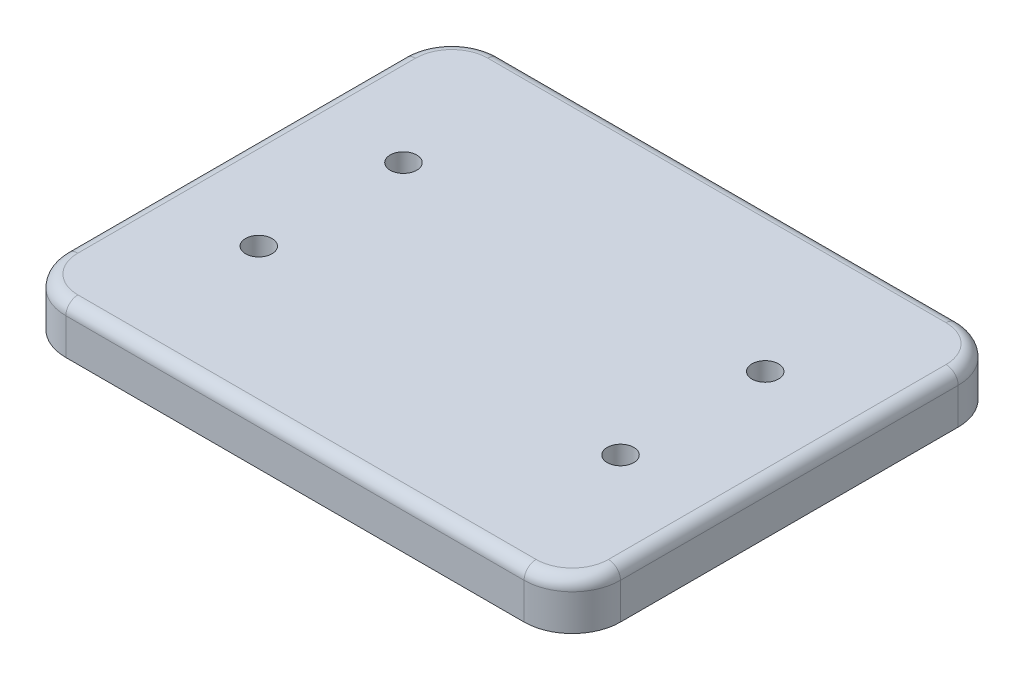
SolidWorks part; units mm, degrees
ref_plane "Front Plane" through (0, 0, 0) normal (0, 0, 1) x (1, 0, 0)
ref_plane "Top Plane" through (0, 0, 0) normal (0, 1, 0) x (1, 0, 0)
ref_plane "Right Plane" through (0, 0, 0) normal (1, 0, 0) x (0, 0, -1)
sketch "Sketch1" plane through (0, 0, 0) normal (0, 1, 0) x (1, 0, 0)
  line L0 (-115, 0) -> (115, 0) construction
  line L1 (-95, 90) -> (95, 90)
  line L2 (-115, 70) -> (-115, -70)
  line L3 (-95, -90) -> (95, -90)
  line L4 (115, 70) -> (115, -70)
  line L5 (-115, 90) -> (115, -90) construction
  line L6 (-115, -90) -> (115, 90) construction
  line L7 (0, 90) -> (0, -90) construction
  arc A0 (-95, -90) -> (-115, -70) centre (-95, -70) cw
  arc A1 (95, -90) -> (115, -70) centre (95, -70) ccw
  arc A2 (95, 90) -> (115, 70) centre (95, 70) cw
  arc A3 (-95, 90) -> (-115, 70) centre (-95, 70) ccw
  point P0 (0, 0)
  dimension "D3" = 20
  dimension "D1" = 230
  dimension "D2" = 180
extrude "Boss-Extrude1" add sketch "Sketch1" along normal blind 20
fillet "Fillet1" radius 5 8 edges at (-115, 20, 0) (-109.1421, 20, -84.1421) (0, 20, -90) (109.1421, 20, -84.1421) (115, 20, 0) (109.1421, 20, 84.1421) (0, 20, 90) (-109.1421, 20, 84.1421)
sketch "Sketch4" plane through (0, 0, 0) normal (0, 1, 0) x (1, 0, 0)
  line L0 (-115, 0) -> (115, 0) construction
  line L1 (0, 90) -> (0, -90) construction
  circle A0 centre (-75, 30) radius 5.5
  circle A1 centre (75, 30) radius 5.5
  dimension "D1" = 11
  dimension "D2" = 30
  dimension "D3" = 75
  dimension "D4" = 75
extrude "Cut-Extrude2" cut sketch "Sketch4" along normal blind 36
sketch "Sketch5" plane through (0, 0, 0) normal (0, -1, 0) x (1, 0, 0)
  circle A0 centre (-75, -30) radius 9
  circle A1 centre (75, -30) radius 9
extrude "Cut-Extrude3" cut sketch "Sketch5" against normal blind 11
mirror "Mirror1" about plane through (0, 0, 0) normal (0, 0, 1) of "Cut-Extrude3", "Cut-Extrude2"
